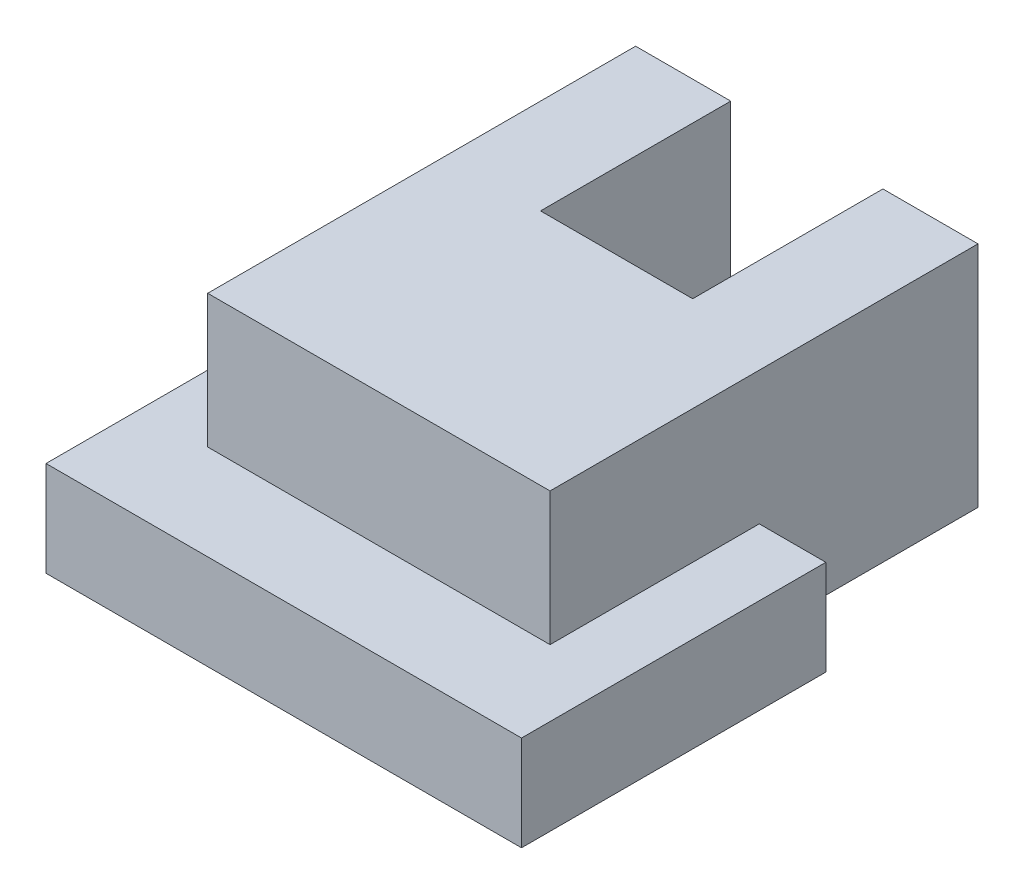
SolidWorks part; units mm, degrees
ref_plane "Alzado" through (0, 0, 0) normal (0, 0, 1) x (1, 0, 0)
ref_plane "Planta" through (0, 0, 0) normal (0, 1, 0) x (1, 0, 0)
ref_plane "Vista lateral" through (0, 0, 0) normal (1, 0, 0) x (0, 0, -1)
sketch "Croquis2" plane through (0, 0, 0) normal (0, 1, 0) x (1, 0, 0)
  line L1 (-25, -16) -> (25, -16)
  line L2 (-25, -16) -> (-25, 16)
  line L3 (-25, 16) -> (25, 16)
  line L4 (25, -16) -> (25, 16)
  line L5 (-25, -16) -> (25, 16) construction
  line L6 (-25, 16) -> (25, -16) construction
  point P0 (0, 0)
  dimension "D1" = 32
  dimension "D2" = 50
extrude "Saliente-Extruir1" add sketch "Croquis2" along normal blind 10
sketch "Croquis3" plane through (0, 10, 0) normal (0, 1, 0) x (1, 0, 0)
  line L0 (8, 39) -> (18, 39)
  line L1 (-18, -6) -> (18, -6)
  line L2 (-18, -6) -> (-18, 39)
  line L3 (-18, 39) -> (-8, 39)
  line L4 (18, -6) -> (18, 39)
  line L6 (-8, 39) -> (-8, 19)
  line L7 (-8, 19) -> (8, 19)
  line L8 (8, 39) -> (8, 19)
  line L9 (25, 16) -> (-25, 16) construction
  point P9 (0, -6)
  dimension "D1" = 16
  dimension "D2" = 20
  dimension "D3" = 36
  dimension "D4" = 45
  dimension "D5" = 22
extrude "Saliente-Extruir2" add sketch "Croquis3" along normal blind 14 and the other way blind 10
